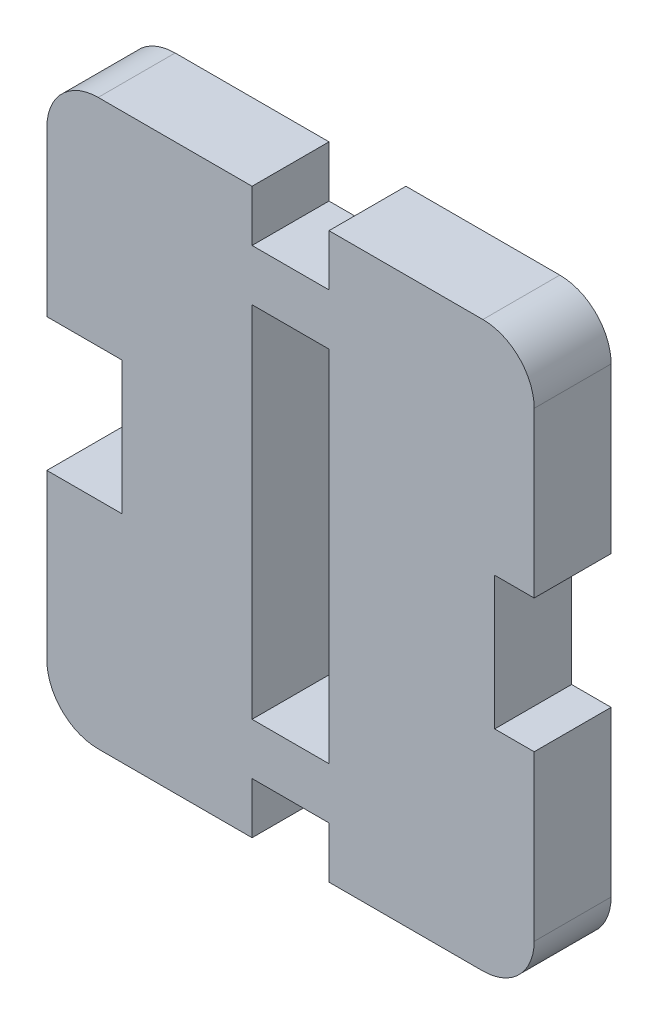
SolidWorks part; units mm, degrees
ref_plane "Front" through (0, 0, 0) normal (0, 0, 1) x (1, 0, 0)
ref_plane "Top" through (0, 0, 0) normal (0, 1, 0) x (1, 0, 0)
ref_plane "Right" through (0, 0, 0) normal (1, 0, 0) x (0, 0, -1)
sketch "Sketch1" plane through (0, 0, 0) normal (0, 0, 1) x (1, 0, 0)
  line L0 (-1044.1169, 51.9977) -> (-1044.1169, 37.9977)
  line L1 (-1049.1904, 44.9977) -> (-1034.6577, 44.9977) construction
  line L2 (-1041.1169, 37.9977) -> (-1041.1169, 51.9977)
  line L3 (-1041.1169, 51.9977) -> (-1044.1169, 51.9977)
  line L4 (-1033.1169, 53.9977) -> (-1033.1169, 47.5931)
  line L5 (-1033.1169, 47.5931) -> (-1034.6577, 47.5931)
  line L6 (-1034.6577, 47.5931) -> (-1034.6577, 42.4024)
  line L7 (-1050.1169, 33.9977) -> (-1044.1169, 33.9977)
  line L8 (-1042.6169, 53.9977) -> (-1041.1169, 53.9977)
  line L9 (-1041.1169, 53.9977) -> (-1041.1169, 55.9977)
  line L10 (-1041.1169, 55.9977) -> (-1035.1169, 55.9977)
  line L11 (-1042.6169, 53.9977) -> (-1044.1169, 53.9977)
  line L12 (-1044.1169, 53.9977) -> (-1044.1169, 55.9977)
  line L13 (-1052.1169, 42.4024) -> (-1052.1169, 35.9977)
  line L14 (-1049.1904, 42.4024) -> (-1052.1169, 42.4024)
  line L15 (-1044.1169, 35.9977) -> (-1044.1169, 33.9977)
  line L16 (-1042.6169, 35.9977) -> (-1044.1169, 35.9977)
  line L17 (-1041.1169, 33.9977) -> (-1035.1169, 33.9977)
  line L18 (-1049.1904, 42.4024) -> (-1049.1904, 47.5931)
  line L19 (-1049.1904, 47.5931) -> (-1052.1169, 47.5931)
  line L20 (-1052.1169, 47.5931) -> (-1052.1169, 53.9977)
  line L21 (-1041.1169, 35.9977) -> (-1041.1169, 33.9977)
  line L22 (-1042.6169, 35.9977) -> (-1041.1169, 35.9977)
  line L23 (-1033.1169, 42.4024) -> (-1034.6577, 42.4024)
  line L24 (-1050.1169, 55.9977) -> (-1044.1169, 55.9977)
  line L25 (-1033.1169, 35.9977) -> (-1033.1169, 42.4024)
  line L26 (-1041.1169, 37.9977) -> (-1044.1169, 37.9977)
  arc A0 (-1052.1169, 53.9977) -> (-1050.1169, 55.9977) centre (-1050.1169, 53.9977) cw
  arc A1 (-1033.1169, 53.9977) -> (-1035.1169, 55.9977) centre (-1035.1169, 53.9977) ccw
  arc A2 (-1033.1169, 35.9977) -> (-1035.1169, 33.9977) centre (-1035.1169, 35.9977) cw
  arc A3 (-1052.1169, 35.9977) -> (-1050.1169, 33.9977) centre (-1050.1169, 35.9977) ccw
  point P8 (-1044.1169, 44.9977)
  point P38 (-1041.1169, 44.9977)
  dimension "D1" = 2
  dimension "D2" = 3
  dimension "D3" = 8
  dimension "D4" = 8
  dimension "D5" = 14
  dimension "D6" = 2
  dimension "D7" = 22
extrude "Base-Extrude" add sketch "Sketch1" along normal blind 3
